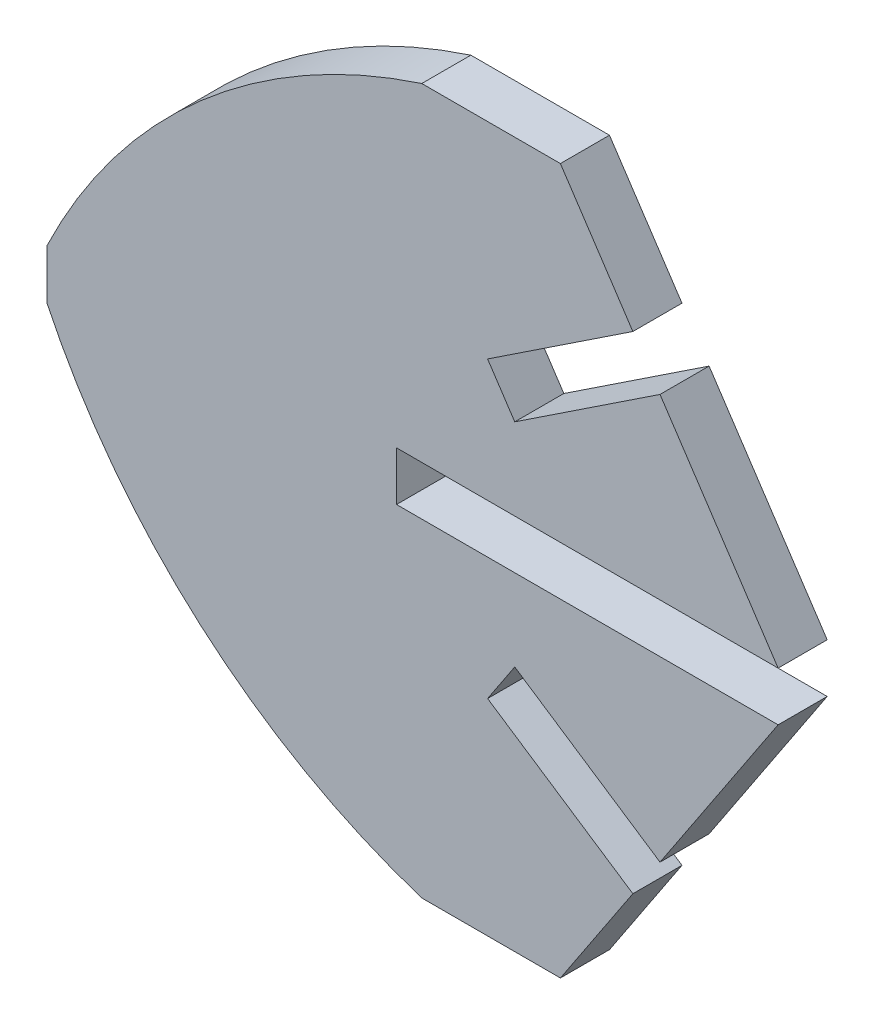
SolidWorks part; units mm, degrees
ref_plane "Front Plane" through (0, 0, 0) normal (0, 0, 1) x (1, 0, 0)
ref_plane "Top Plane" through (0, 0, 0) normal (0, 1, 0) x (1, 0, 0)
ref_plane "Right Plane" through (0, 0, 0) normal (1, 0, 0) x (0, 0, -1)
sketch "Sketch1" plane through (0, 0, 0) normal (0, 0, 1) x (1, 0, 0)
  line L0 (90.4592, -1.524) -> (102.3071, -1.524)
  line L1 (102.3071, -1.524) -> (98.6403, -7.0506)
  line L2 (97.7977, -8.3205) -> (95.5473, -11.7123)
  line L3 (95.5473, 10.1883) -> (91.2426, 10.1883)
  line L4 (79.6004, -1.524) -> (79.6004, 0)
  line L5 (79.6004, -1.524) -> (79.6004, 0) construction
  line L6 (79.6004, -0.762) -> (70.0543, -0.762) construction
  line L7 (90.4592, -1.524) -> (90.4592, 0)
  line L8 (90.4592, -1.524) -> (90.4592, 0) construction
  line L9 (98.6403, -7.0506) -> (94.1297, -4.0579)
  line L10 (97.7977, -8.3205) -> (93.2871, -5.3278)
  line L11 (94.1297, 2.5339) -> (93.2871, 3.8038)
  line L12 (95.5473, -11.7123) -> (91.2426, -11.7123)
  line L13 (94.1297, -4.0579) -> (93.2871, -5.3278)
  line L15 (97.7977, 6.7965) -> (93.2871, 3.8038)
  line L16 (98.6403, 5.5266) -> (94.1297, 2.5339)
  line L18 (97.7977, 6.7965) -> (95.5473, 10.1883)
  line L19 (102.3071, 0) -> (98.6403, 5.5266)
  line L20 (90.4592, 0) -> (102.3071, 0)
  arc A0 (91.2426, -11.7123) -> (79.6004, -1.524) centre (97.295, 6.9497) cw
  arc A1 (91.2426, 10.1883) -> (79.6004, 0) centre (97.295, -8.4737) ccw
  point P22 (90.4592, -0.762)
extrude "Boss-Extrude1" add sketch "Sketch1" along normal blind 1.524
